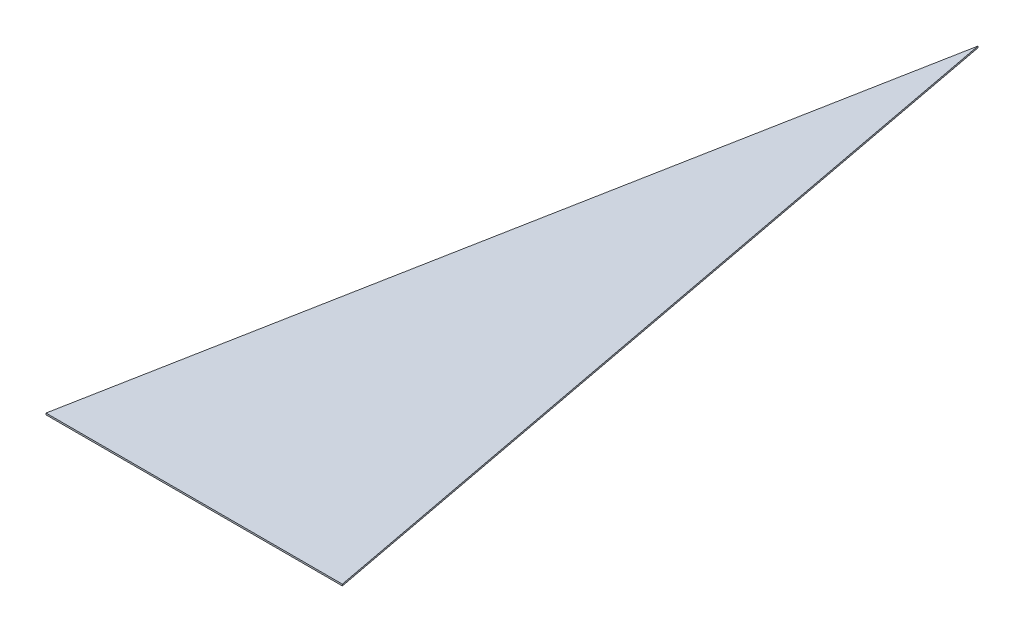
SolidWorks part; units mm, degrees
ref_plane "Front Plane" through (0, 0, 0) normal (0, 0, 1) x (1, 0, 0)
ref_plane "Top Plane" through (0, 0, 0) normal (0, 1, 0) x (1, 0, 0)
ref_plane "Right Plane" through (0, 0, 0) normal (1, 0, 0) x (0, 0, -1)
sketch "Sketch1" plane through (0, 0, 0) normal (0, 0, 1) x (1, 0, 0)
  line L0 (0, 0) -> (0, 3352.8)
  line L1 (0, 0) -> (2813.3332, 0)
  line L2 (2813.3332, 0) -> (0, 3352.8)
  dimension "D1" = 3352.8
  dimension "D2" = 50
sketch "Sketch7" plane through (0, 0, 0) normal (0, 1, 0) x (1, 0, 0)
  line L0 (0, 12192) -> (2813.3332, -2689.5552)
  line L1 (2813.3332, -2689.5552) -> (-2813.3332, -2689.5552)
  line L2 (-2813.3332, -2689.5552) -> (0, 12192)
  point P2 (0, 9135.9195)
  point P4 (0, -2689.5552)
  dimension "D1" = 5626.6665
  dimension "D2" = 2689.5552
  dimension "D3" = 12192
extrude "Boss-Extrude1" add sketch "Sketch7" along normal blind 30.48
equation "\"D1@Sketch1\"=\"z\""
equation "\"z\"= 11'input from front view aircraft, 5 degree clearance"
equation "\"angle\"= 50'maximum 63 degree"
equation "\"D2@Sketch1\"=\"angle\""
equation "\"D1@Sketch7\"=\"z\"/tan( \"angle\")*2"
